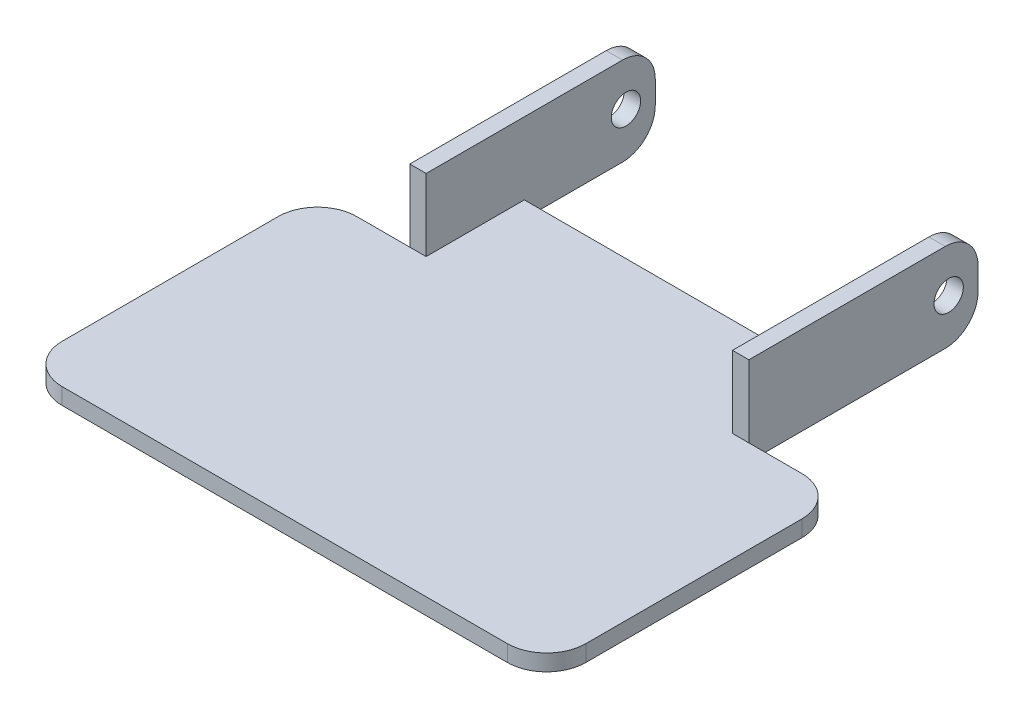
SolidWorks part; units mm, degrees
ref_plane "Front Plane" through (0, 0, 0) normal (0, 0, 1) x (1, 0, 0)
ref_plane "Top Plane" through (0, 0, 0) normal (0, 1, 0) x (1, 0, 0)
ref_plane "Right Plane" through (0, 0, 0) normal (1, 0, 0) x (0, 0, -1)
sketch "Sketch1" plane through (0, 0, 0) normal (0, 1, 0) x (1, 0, 0)
  line L0 (8.9535, 28.575) -> (8.9535, 50.8)
  line L1 (0, 0) -> (50.8, 0)
  line L2 (0, 0) -> (0, 28.575)
  line L3 (0, 28.575) -> (8.9535, 28.575)
  line L4 (50.8, 0) -> (50.8, 28.575)
  line L5 (8.9535, 50.8) -> (10.541, 50.8)
  line L6 (10.541, 50.8) -> (10.541, 38.1)
  line L7 (10.541, 38.1) -> (40.259, 38.1)
  line L8 (40.259, 38.1) -> (40.259, 50.8)
  line L9 (40.259, 50.8) -> (41.8465, 50.8)
  line L10 (41.8465, 50.8) -> (41.8465, 28.575)
  line L11 (41.8465, 28.575) -> (50.8, 28.575)
  dimension "D1" = 1.5875
  dimension "D2" = 50.8
  dimension "D3" = 28.575
  dimension "D4" = 38.1
  dimension "D5" = 32.893
  dimension "D6" = 50.8
extrude "Boss-Extrude1" add sketch "Sketch1" along normal blind 1.5875
sketch "Sketch2" plane through (0, 1.5875, 0) normal (0, 1, 0) x (1, 0, 0)
  line L1 (8.9535, 28.575) -> (10.541, 28.575)
  line L2 (8.9535, 28.575) -> (8.9535, 50.8)
  line L3 (8.9535, 50.8) -> (10.541, 50.8)
  line L4 (10.541, 28.575) -> (10.541, 50.8)
  line L5 (41.8465, 28.575) -> (40.259, 28.575)
  line L6 (41.8465, 28.575) -> (41.8465, 50.8)
  line L7 (41.8465, 50.8) -> (40.259, 50.8)
  line L8 (40.259, 28.575) -> (40.259, 50.8)
extrude "Boss-Extrude2" add sketch "Sketch2" along normal blind 6.985
fillet "Fillet1" radius 3.175 4 edges at (41.0527, 8.5725, -50.8) (41.0527, 0, -50.8) (9.7472, 8.5725, -50.8) (9.7472, 0, -50.8)
fillet "Fillet2" radius 3.81 4 edges at (0, 0.7937, -28.575) (0, 0.7937, 0) (50.8, 0.7937, 0) (50.8, 0.7937, -28.575)
hole_wizard "Hole1" positions "Sketch4" profile "Sketch3" legacy end condition through all
sketch "Sketch4" plane through (8.9535, 0, 0) normal (-1, 0, 0) x (0, 0, 1)
  line L0 (-50.8, 4.2862) -> (-28.575, 4.2862) construction
  line L1 (-50.8, 5.3975) -> (-50.8, 3.175) construction
  line L2 (-28.575, 8.5725) -> (-28.575, 1.5875) construction
  point P0 (-47.9552, 4.2862)
  dimension "D1" = 2.8448
sketch "Sketch3" plane through (8.9535, 4.2862, -47.9552) normal (0, 1, 0) x (0, 0, 1)
  line L0 (0, 0) -> (0, 41.8465)
  line L1 (0, 41.8465) -> (1.4224, 41.8465)
  line L2 (1.4224, 41.8465) -> (1.4224, 0)
  line L3 (1.4224, 0) -> (0, 0)
  line L4 (0, 110) -> (0, -10) construction
  dimension "Diameter" = 2.8448
  dimension "Depth" = 41.8465
